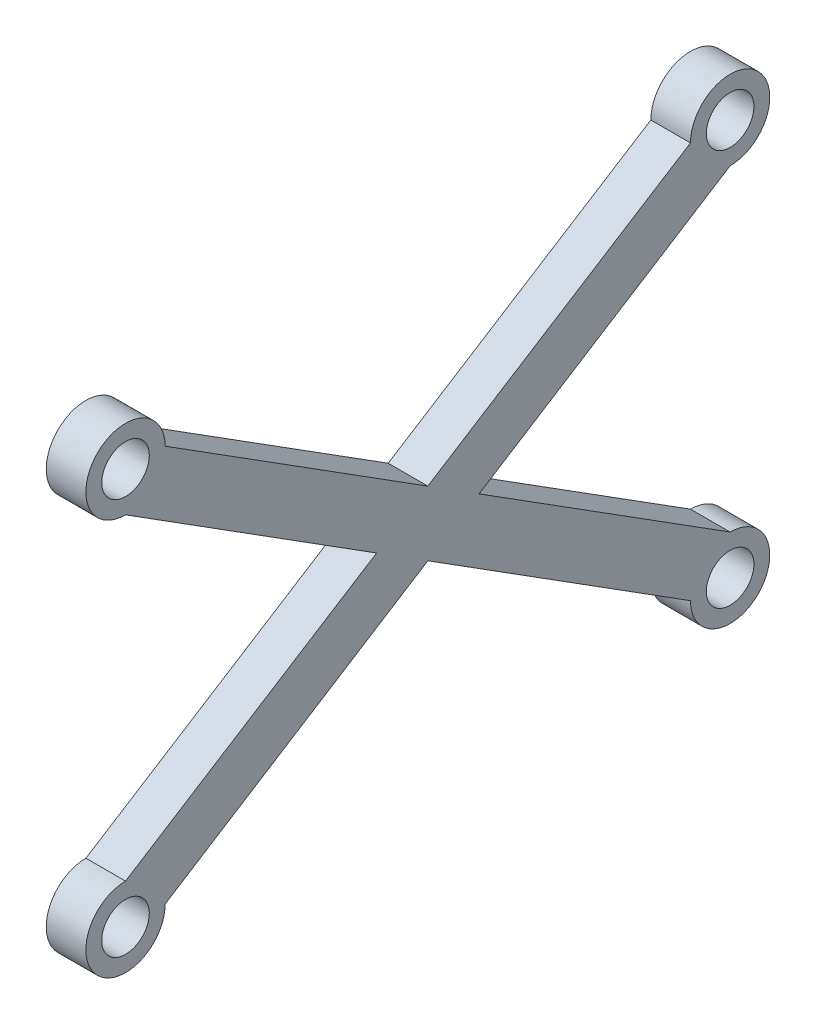
SolidWorks part; units mm, degrees
material "Rubber"
ref_plane "Front Plane" through (0, 0, 0) normal (1, 0, 0) x (0, 1, 0)
ref_plane "Top Plane" through (0, 0, 0) normal (0, 0, 1) x (0, 1, 0)
ref_plane "Right Plane" through (0, 0, 0) normal (0, 1, 0) x (-1, 0, 0)
other "Rubber"
sketch "Sketch1" plane through (0, 0, 0) normal (1, 0, 0) x (0, 1, 0)
  line L0 (-10, 13.25) -> (-1.6316, 0)
  line L5 (-1.6316, 0) -> (-10, -13.25)
  line L6 (1.6316, 0) -> (10, 13.25)
  line L7 (-8, -15.25) -> (0, -2.5833)
  line L8 (8, 15.25) -> (0, 2.5833)
  line L9 (-8, 15.25) -> (0, 2.5833)
  line L10 (1.6316, 0) -> (10, -13.25)
  line L11 (0, -2.5833) -> (8, -15.25)
  arc A0 (-8, 15.25) -> (-10, 13.25) centre (-10, 15.25) ccw
  arc A1 (10, 13.25) -> (8, 15.25) centre (10, 15.25) ccw
  arc A2 (8, -15.25) -> (10, -13.25) centre (10, -15.25) ccw
  arc A3 (-10, -13.25) -> (-8, -15.25) centre (-10, -15.25) ccw
  point P0 (0, 0)
  dimension "D3" = 2
  dimension "D4" = 2
extrude "Boss-Extrude1" add sketch "Sketch1" along normal blind 2
hole_wizard "M2 Clearance Hole1" positions "Sketch3" profile "Sketch5" hole size "M2" standard "ANSI Metric" end condition through all
sketch "Sketch3" plane through (2, 0, 0) normal (1, 0, 0) x (0, 0, -1)
  point P0 (15.25, 10)
  point P3 (15.25, -10)
  point P6 (-15.25, 10)
  point P9 (-15.25, -10)
sketch "Sketch5" plane through (2, 10, -15.25) normal (0, 1, 0) x (0, 0, -1)
  line L0 (0, 0) -> (0, 2)
  line L1 (0, 2) -> (1.2, 2)
  line L2 (1.2, 2) -> (1.2, 0)
  line L5 (1.2, 0) -> (0, 0)
  line L11 (0, -6.35) -> (0, 107.95) construction
  dimension "Thru Hole Dia." = 2.4
  dimension "Thru Hole Depth" = 2
